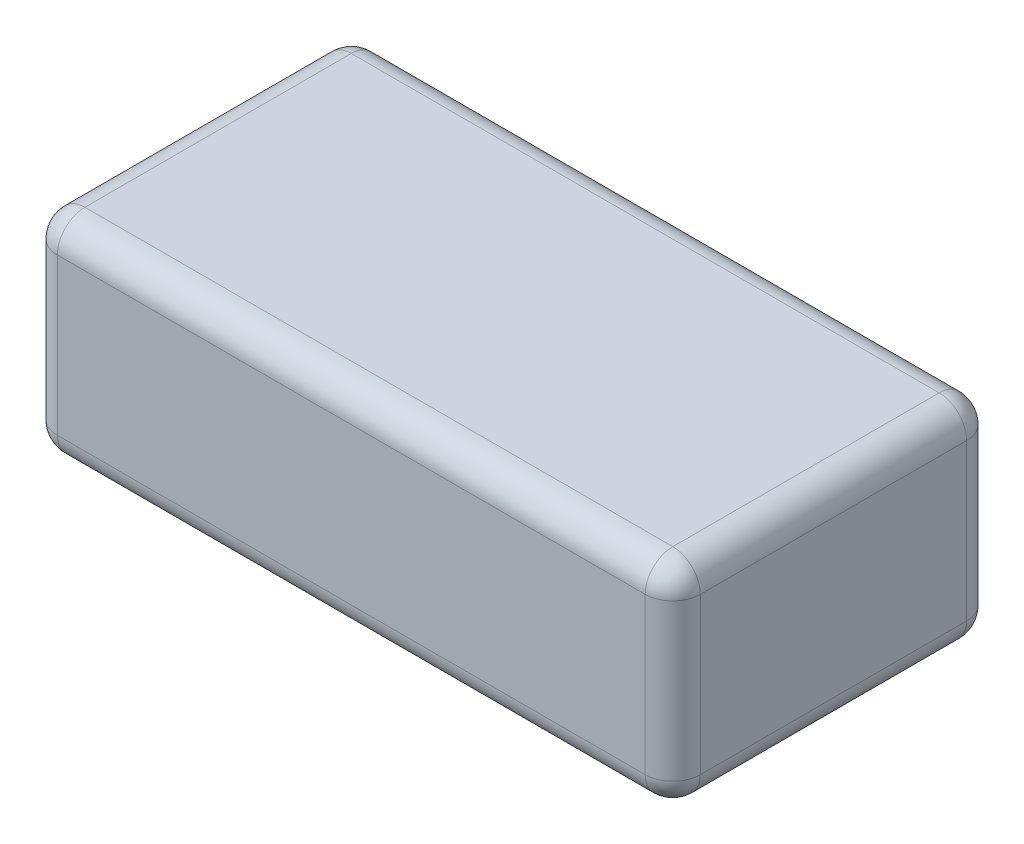
SolidWorks part; units mm, degrees
ref_plane "Front Plane" through (0, 0, 0) normal (0, 0, 1) x (1, 0, 0)
ref_plane "Top Plane" through (0, 0, 0) normal (0, 1, 0) x (1, 0, 0)
ref_plane "Right Plane" through (0, 0, 0) normal (1, 0, 0) x (0, 0, -1)
other "Center of Mass"
sketch "Sketch1" plane through (0, 0, 0) normal (0, 0, 1) x (1, 0, 0)
  line L0 (45.6632, 0) -> (-41.6569, 0) construction
  line L1 (-35, 11.5) -> (35, 11.5)
  line L2 (-35, 11.5) -> (-35, -11.5)
  line L3 (-35, -11.5) -> (35, -11.5)
  line L4 (35, 11.5) -> (35, -11.5)
  line L5 (0, 22.4676) -> (0, -28.3086) construction
  point P4 (0, 11.5)
  point P10 (35, 0)
  dimension "D1" = 70
  dimension "D2" = 23
extrude "Boss-Extrude1" add sketch "Sketch1" along normal mid plane 35 contours L2 L1 L4 L3
fillet "Fillet1" radius 3 12 edges at (35, -11.5, 0) (35, 11.5, 0) (-35, 11.5, 0) (-35, -11.5, 0) (-35, 0, 17.5) (0, 11.5, 17.5) (35, 0, 17.5) (0, -11.5, 17.5) (35, 0, -17.5) (0, 11.5, -17.5) (-35, 0, -17.5) (0, -11.5, -17.5)
